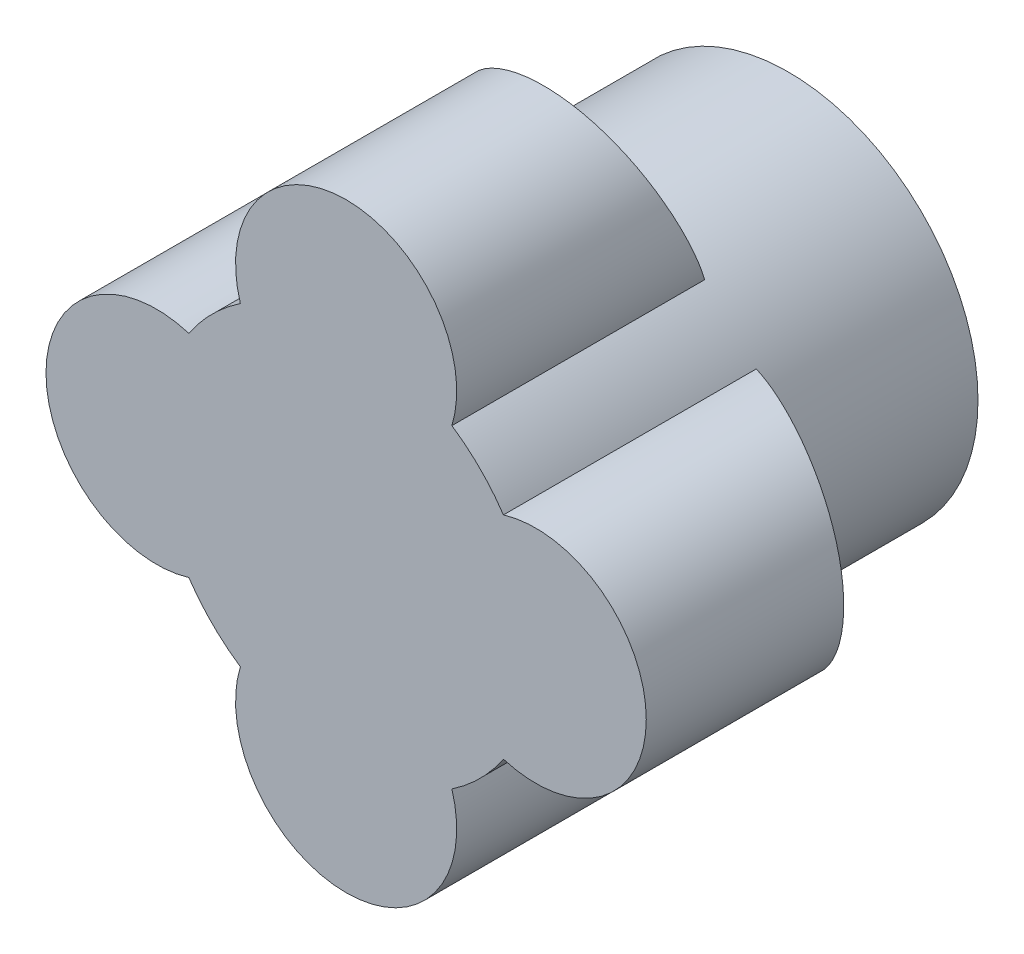
SolidWorks part; units mm, degrees
ref_plane "前视基准面" through (0, 0, 0) normal (0, 0, 1) x (1, 0, 0)
ref_plane "上视基准面" through (0, 0, 0) normal (0, 1, 0) x (1, 0, 0)
ref_plane "右视基准面" through (0, 0, 0) normal (1, 0, 0) x (0, 0, -1)
sketch "草图1" plane through (0, 0, 0) normal (0, 0, 1) x (1, 0, 0)
  arc A0 (167.391, -248.9583) -> (248.9583, -167.391) centre (0, 0) ccw
  arc A1 (248.9583, -167.391) -> (248.9583, 167.391) centre (300, 0) ccw
  arc A2 (-167.391, -248.9583) -> (167.391, -248.9583) centre (0, -300) ccw
  arc A3 (-248.9583, 167.391) -> (-248.9583, -167.391) centre (-300, 0) ccw
  arc A4 (167.391, 248.9583) -> (-167.391, 248.9583) centre (0, 300) ccw
  arc A5 (-248.9583, -167.391) -> (-167.391, -248.9583) centre (0, 0) ccw
  arc A6 (-167.391, 248.9583) -> (-248.9583, 167.391) centre (0, 0) ccw
  arc A7 (248.9583, 167.391) -> (167.391, 248.9583) centre (0, 0) ccw
  point P14 (0, 0)
  dimension "D1" = 4
  dimension "D2" = 300
  dimension "D3" = 175
extrude "凸台-拉伸1" add sketch "草图1" along normal blind 700
sketch "草图2" plane through (0, 0, 0) normal (0, 1, 0) x (1, 0, 0)
  line L2 (500, -400) -> (500, 0)
  line L3 (500, 0) -> (300, 0)
  line L4 (175, 0) -> (-175, 0) construction
  line L5 (300, 0) -> (300, -300)
  line L6 (300, -300) -> (500, -400)
  dimension "D1" = 300
  dimension "D2" = 500
  dimension "D3" = 400
  dimension "D4" = 300
ref_axis "基准轴1" through (0, 0, 700) along (0, 0, -1)
revolve "切除-旋转1" cut sketch "草图2" angle 360 about axis through (0, 0, 700) along (0, 0, -1)
